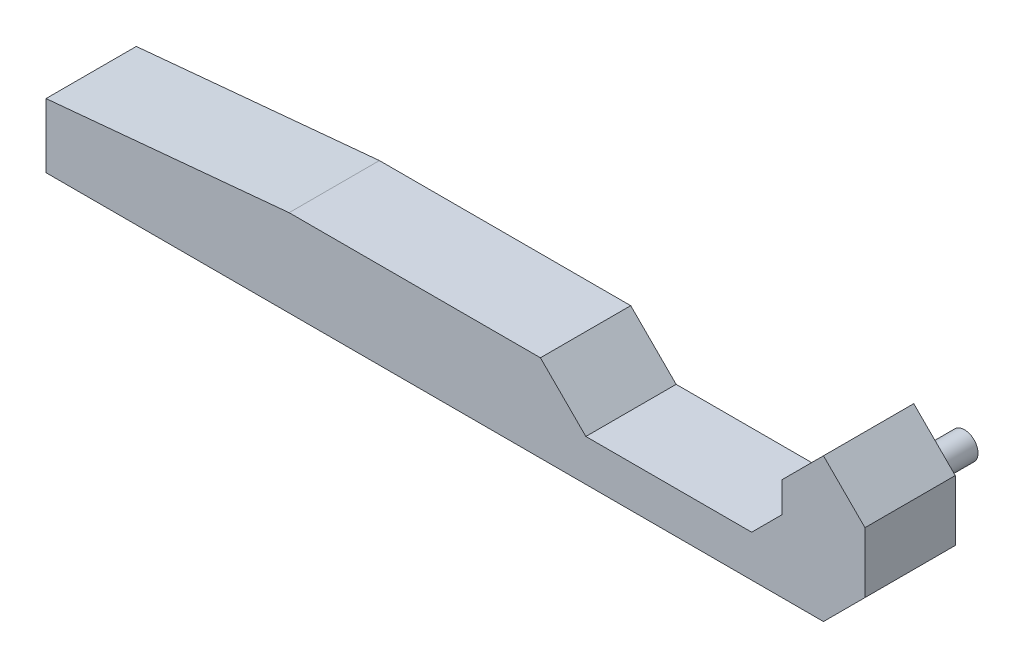
SolidWorks part; units mm, degrees
ref_plane "Front Plane" through (0, 0, 0) normal (0, 0, 1) x (1, 0, 0)
ref_plane "Top Plane" through (0, 0, 0) normal (0, 1, 0) x (1, 0, 0)
ref_plane "Right Plane" through (0, 0, 0) normal (1, 0, 0) x (0, 0, -1)
sketch "Sketch1" plane through (0, 0, 0) normal (0, 0, 1) x (1, 0, 0)
  line L0 (0, 0) -> (0, -6.7092)
  line L1 (0, -6.7092) -> (-4.5973, -11.3065)
  line L2 (-4.5973, -11.3065) -> (-57.2299, -11.3065)
  line L3 (0, 0) -> (-4.5973, 4.5973)
  line L4 (-4.5973, 4.5973) -> (-9.1946, 0)
  line L5 (-9.1946, 0) -> (-9.1946, -3.3546)
  line L6 (-9.1946, -3.3546) -> (-12.5492, -6.7092)
  line L7 (-12.5492, -6.7092) -> (-30.9136, -6.7092)
  line L8 (-30.9136, -6.7092) -> (-35.9455, -1.6773)
  line L9 (-35.9455, -1.6773) -> (-49.5885, -1.6773)
  line L10 (-49.5885, -1.6773) -> (-63.7796, -1.6773)
  line L11 (-63.7796, -1.6773) -> (-90.7065, -4.1932)
  line L12 (-57.2299, -11.3065) -> (-83.7928, -11.3065)
  line L13 (-83.7928, -11.3065) -> (-90.7065, -11.3065)
  line L14 (-90.7065, -11.3065) -> (-90.7065, -4.1932)
extrude "Boss-Extrude1" add sketch "Sketch1" along normal blind 10
sketch "Sketch2" plane through (0, 0, 0) normal (0, 0, -1) x (-1, 0, 0)
  circle A0 centre (3.9815, -1.5914) radius 1.5
  dimension "D1" = 3
extrude "Boss-Extrude2" add sketch "Sketch2" along normal blind 5
